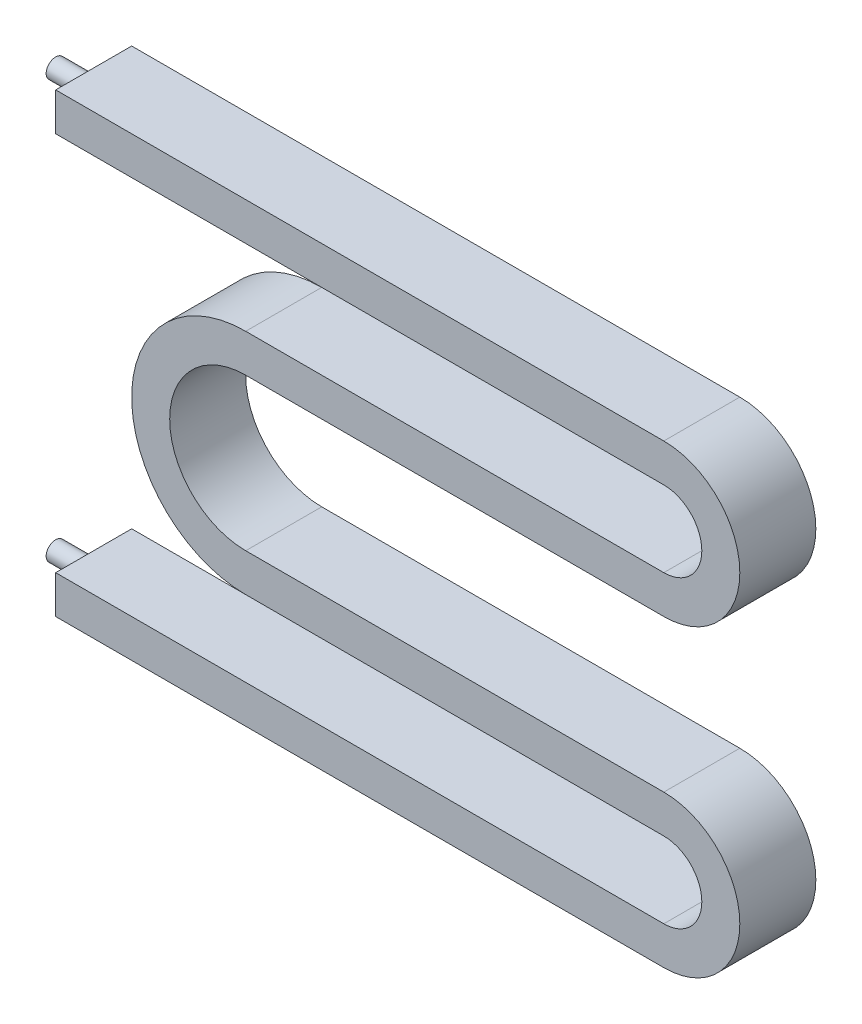
SolidWorks part; units mm, degrees
ref_plane "Alzado" through (0, 0, 0) normal (0, 0, 1) x (1, 0, 0)
ref_plane "Planta" through (0, 0, 0) normal (0, 1, 0) x (1, 0, 0)
ref_plane "Vista lateral" through (0, 0, 0) normal (1, 0, 0) x (0, 0, -1)
sketch "Sketch1" plane through (0, 0, 0) normal (0, 0, 1) x (1, 0, 0)
  line L0 (0, 0) -> (80, 0)
  line L1 (80, -20) -> (25, -20)
  line L2 (25, -40) -> (80, -40)
  line L3 (80, -60) -> (0, -60)
  line L4 (0, -5) -> (80, -5)
  line L5 (80, -15) -> (25, -15)
  line L6 (25, -45) -> (80, -45)
  line L7 (80, -55) -> (0, -55)
  line L8 (0, 0) -> (0, -5)
  line L9 (0, -55) -> (0, -60)
  arc A0 (80, 0) -> (80, -20) centre (80, -10) cw
  arc A1 (25, -20) -> (25, -40) centre (25, -30) ccw
  arc A2 (80, -40) -> (80, -60) centre (80, -50) cw
  arc A3 (80, -5) -> (80, -15) centre (80, -10) cw
  arc A4 (25, -15) -> (25, -45) centre (25, -30) ccw
  arc A5 (80, -45) -> (80, -55) centre (80, -50) cw
  dimension "D1" = 10
  dimension "D2" = 10
  dimension "D3" = 10
  dimension "D4" = 80
  dimension "D5" = 55
  dimension "D6" = 55
  dimension "D7" = 5
extrude "Boss-Extrude1" add sketch "Sketch1" along normal blind 10
sketch "Sketch2" plane through (0, 0, 0) normal (-1, 0, 0) x (0, 0, 1)
  line L0 (5, -5) -> (5, 0) construction
  line L1 (10, -5) -> (0, -5) construction
  line L2 (10, 0) -> (0, 0) construction
  circle A0 centre (5, -2.5) radius 1.25
  dimension "D1" = 2.5
extrude "Boss-Extrude2" add sketch "Sketch2" along normal blind 5
sketch "Sketch3" plane through (0, 0, 0) normal (-1, 0, 0) x (0, 0, 1)
  line L0 (5, -60) -> (5, -55) construction
  line L1 (10, -60) -> (0, -60) construction
  line L2 (10, -55) -> (0, -55) construction
  circle A0 centre (5, -57.5) radius 1.25
  dimension "D1" = 2.5
extrude "Boss-Extrude3" add sketch "Sketch3" along normal blind 5
